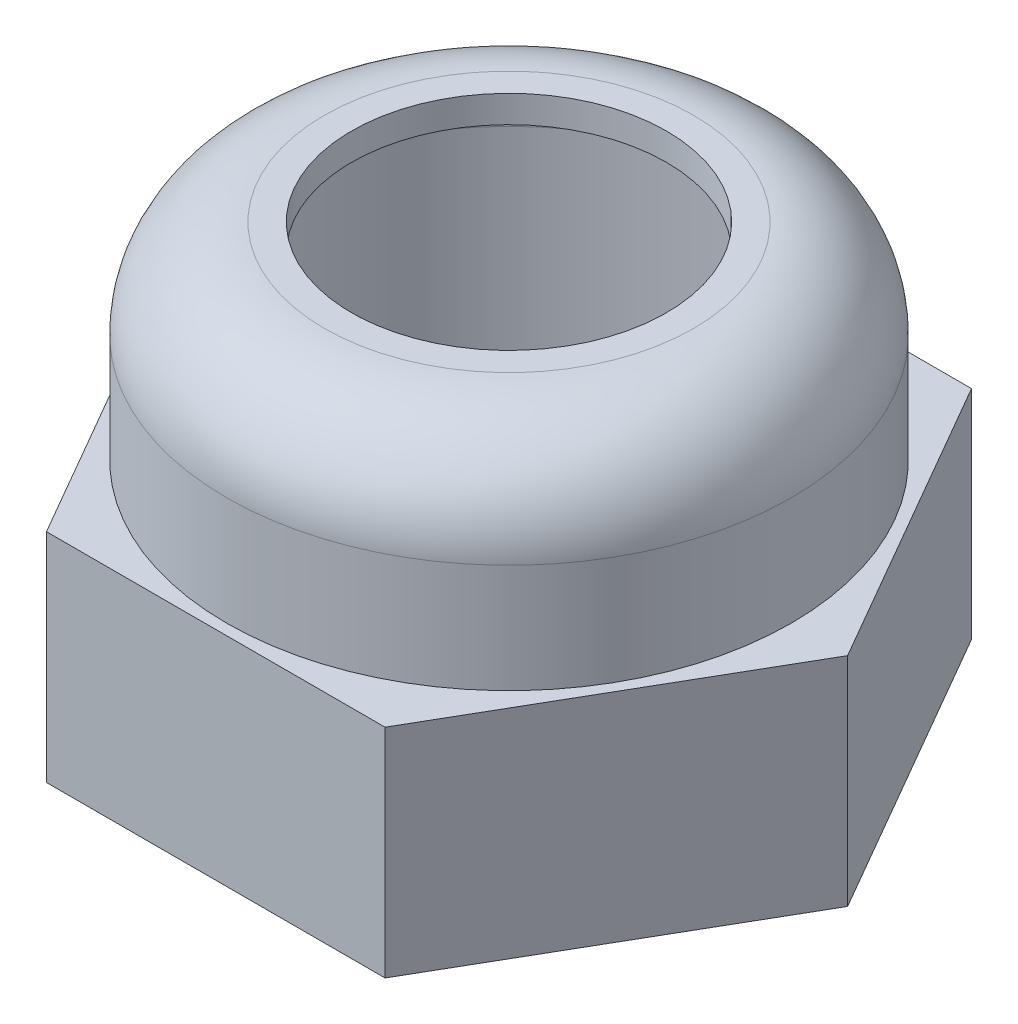
SolidWorks part; units mm, degrees
material "PVC hart"
ref_plane "Ebene vorne" through (0, 0, 0) normal (0, 0, 1) x (1, 0, 0)
ref_plane "Ebene oben" through (0, 0, 0) normal (0, 1, 0) x (1, 0, 0)
ref_plane "Ebene rechts" through (0, 0, 0) normal (1, 0, 0) x (0, 0, -1)
sketch "Skizze1" plane through (0, 0, 0) normal (0, 1, 0) x (1, 0, 0)
  line L1 (15.5885, 0) -> (7.7942, 13.5)
  line L2 (7.7942, 13.5) -> (-7.7942, 13.5)
  line L3 (-7.7942, 13.5) -> (-15.5885, 0)
  line L4 (-15.5885, 0) -> (-7.7942, -13.5)
  line L5 (-7.7942, -13.5) -> (7.7942, -13.5)
  line L6 (7.7942, -13.5) -> (15.5885, 0)
  circle A0 centre (0, 0) radius 11.75
  circle A1 centre (0, 0) radius 13.5 construction
  dimension "D1" = 23.5
  dimension "D2" = 27
extrude "Aufsatz-Linear austragen1" add sketch "Skizze1" along normal blind 10
sketch "Skizze2" plane through (0, 10, 0) normal (0, 1, 0) x (1, 0, 0)
  circle A0 centre (0, 0) radius 11.75
  circle A1 centre (0, 0) radius 11.75 construction
  circle A2 centre (0, 0) radius 13
  dimension "D1" = 26
extrude "Aufsatz-Linear austragen2" add sketch "Skizze2" along normal blind 5
sketch "Skizze3" plane through (0, 0, 0) normal (0, 0, 1) x (1, 0, 0)
  line L0 (0, 0) -> (0, 50000) construction
  line L1 (11.75, 15) -> (-11.75, 15) construction
  line L2 (-13, 15) -> (-11.75, 15)
  line L3 (0, 15) -> (-7.25, 15) construction
  line L4 (0, 15) -> (0, 19.5) construction
  line L5 (0, 19.5) -> (-7.25, 19.5) construction
  line L6 (-7.25, 15) -> (-7.25, 19.5) construction
  line L7 (-8.5, 19.5) -> (-7.25, 19.5)
  line L8 (-13, 15) -> (-8.5, 15) construction
  line L9 (-13, 15) -> (-13, 19.5) construction
  line L10 (-13, 19.5) -> (-8.5, 19.5) construction
  line L11 (-8.5, 15) -> (-8.5, 19.5) construction
  line L12 (-7.25, 19.5) -> (-7.25, 18.25)
  line L13 (-7.25, 18.25) -> (-8.5, 18.25)
  arc A0 (-13, 15) -> (-8.5, 19.5) centre (-8.5, 15) cw
  arc A1 (-11.75, 15) -> (-8.5, 18.25) centre (-8.5, 15) cw
  point P3 (0, 15)
  dimension "D3" = 3.25
  dimension "D1" = 7.25
  dimension "D2" = 4.5
revolve "Rotation1" add sketch "Skizze3" angle 360 about L0
